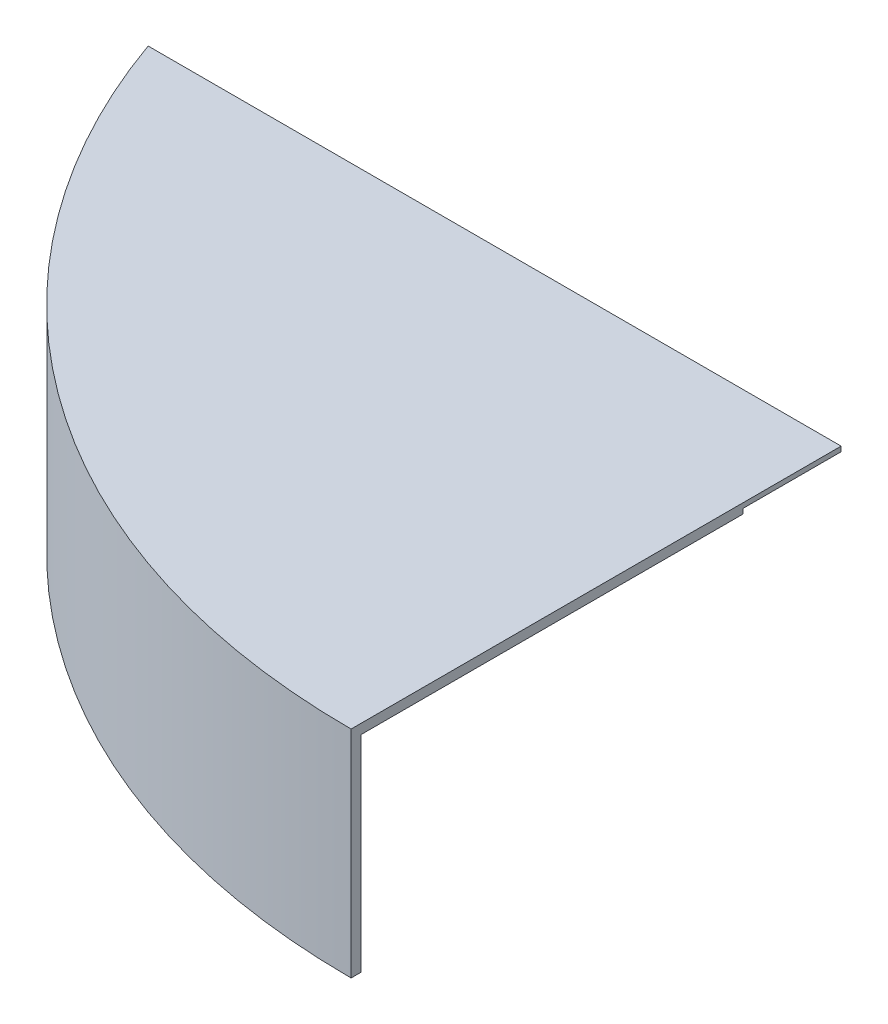
SolidWorks part; units mm, degrees
ref_plane "Front Plane" through (0, 0, 0) normal (0, 0, 1) x (1, 0, 0)
ref_plane "Top Plane" through (0, 0, 0) normal (0, 1, 0) x (1, 0, 0)
ref_plane "Right Plane" through (0, 0, 0) normal (1, 0, 0) x (0, 0, -1)
sketch "Sketch1" plane through (0, 0, 0) normal (0, 1, 0) x (1, 0, 0)
  line L0 (0, -50) -> (0, -150)
  line L2 (0, -50) -> (-141.4214, -50)
  arc A0 (-141.4214, -50) -> (0, -150) centre (0, 0) ccw
  point P5 (0, -50)
  dimension "D1" = 300
  dimension "D2" = 100
extrude "Boss-Extrude1" add sketch "Sketch1" along normal blind 44
shell "Shell1" thickness 2
sketch "Sketch3" plane through (0, 42, 0) normal (0, -1, 0) x (1, 0, 0)
  line L0 (-139.2982, 50) -> (0, 50)
  line L1 (0, 50) -> (0, 70)
  line L2 (0, 148) -> (0, 50) construction
  line L3 (0, 70) -> (-130.3994, 70)
  arc A0 (0, 148) -> (-139.2982, 50) centre (0, 0) ccw construction
  arc A1 (-130.3994, 70) -> (-139.2982, 50) centre (0, 0) ccw
  dimension "D1" = 20
extrude "Cut-Extrude1" cut sketch "Sketch3" against normal blind 1
